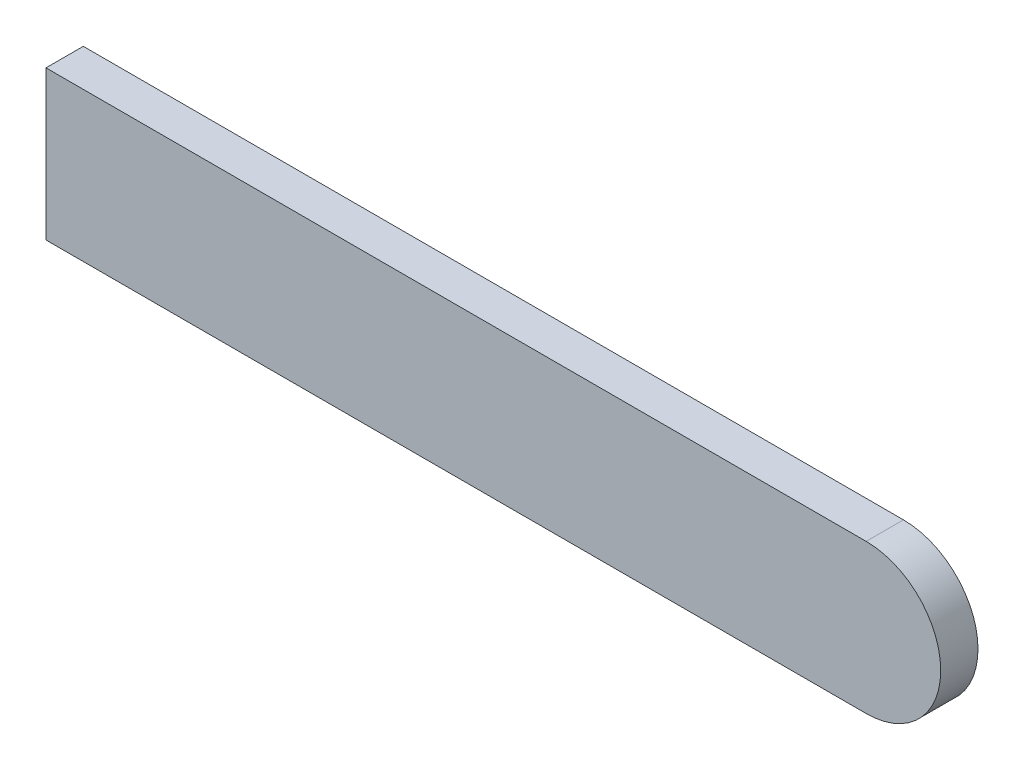
SolidWorks part; units mm, degrees
ref_plane "Front Plane" through (0, 0, 0) normal (0, 0, 1) x (1, 0, 0)
ref_plane "Top Plane" through (0, 0, 0) normal (0, 1, 0) x (1, 0, 0)
ref_plane "Right Plane" through (0, 0, 0) normal (1, 0, 0) x (0, 0, -1)
sketch "Sketch1" plane through (0, 0, 0) normal (0, 0, 1) x (1, 0, 0)
  line L1 (-35, 10) -> (75, 10)
  line L2 (-35, 10) -> (-35, -10)
  line L3 (-35, -10) -> (75, -10)
  arc A0 (75, -10) -> (75, 10) centre (75, 0) ccw
  dimension "D5" = 20
  dimension "D1" = 20
  dimension "D2" = 10
  dimension "D3" = 110
  dimension "D4" = 35
extrude "Boss-Extrude1" add sketch "Sketch1" along normal blind 5
